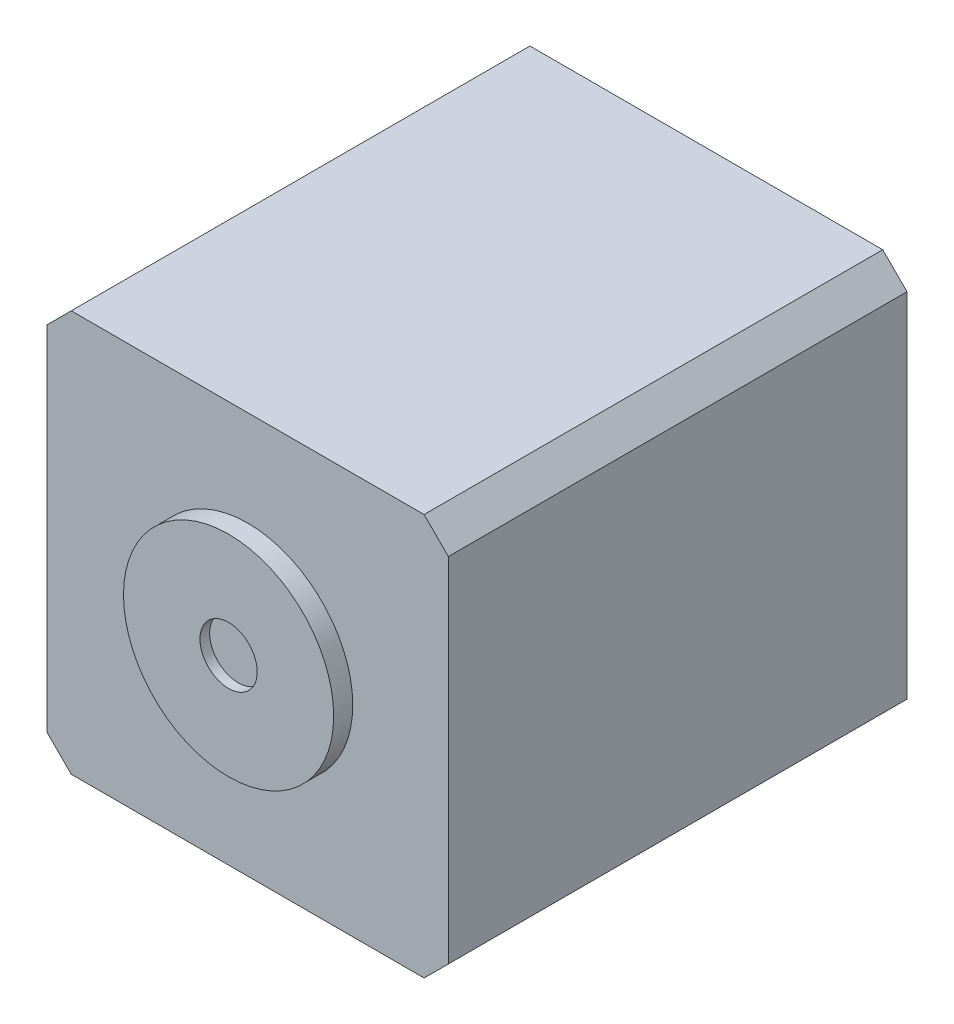
SolidWorks part; units mm, degrees
ref_plane "Front Plane" through (0, 0, 0) normal (0, 0, 1) x (1, 0, 0)
ref_plane "Top Plane" through (0, 0, 0) normal (0, 1, 0) x (1, 0, 0)
ref_plane "Right Plane" through (0, 0, 0) normal (1, 0, 0) x (0, 0, -1)
sketch "Sketch1" plane through (0, 0, 0) normal (0, 0, 1) x (1, 0, 0)
  line L1 (21.0058, -21.0058) -> (-21.0058, -21.0058)
  line L2 (21.0058, -21.0058) -> (21.0058, 21.0058)
  line L3 (21.0058, 21.0058) -> (-21.0058, 21.0058)
  line L4 (-21.0058, -21.0058) -> (-21.0058, 21.0058)
  line L5 (21.0058, -21.0058) -> (-21.0058, 21.0058) construction
  line L6 (21.0058, 21.0058) -> (-21.0058, -21.0058) construction
  point P0 (0, 0)
  dimension "D1" = 42.0116
extrude "Boss-Extrude1" add sketch "Sketch1" along normal blind 48.006
chamfer "Chamfer1" distance 2.54 angle 45 4 edges at (21.0058, -21.0058, 24.003) (-21.0058, -21.0058, 24.003) (21.0058, 21.0058, 24.003) (-21.0058, 21.0058, 24.003)
sketch "Sketch2" plane through (0, 0, 48.006) normal (0, 0, 1) x (1, 0, 0)
  circle A0 centre (0, 0) radius 10.9982
  dimension "D1" = 21.9964
extrude "Boss-Extrude2" add sketch "Sketch2" along normal blind 1.999
sketch "Sketch3" plane through (0, 0, 50.005) normal (0, 0, 1) x (1, 0, 0)
  circle A0 centre (0, 0) radius 2.9972
  dimension "D1" = 5.9944
extrude "Cut-Extrude1" cut sketch "Sketch3" against normal blind 1.016
